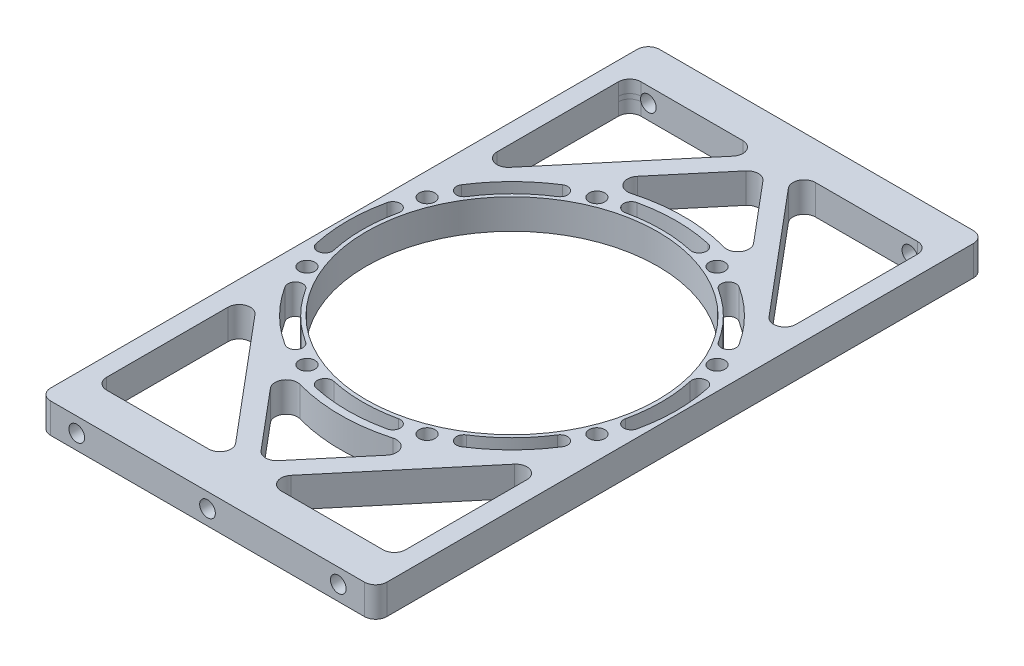
SolidWorks part; units mm, degrees
material "6063-O"
ref_plane "前视基准面" through (0, 0, 0) normal (0, 0, 1) x (1, 0, 0)
ref_plane "上视基准面" through (0, 0, 0) normal (0, 1, 0) x (1, 0, 0)
ref_plane "右视基准面" through (0, 0, 0) normal (1, 0, 0) x (0, 0, -1)
sketch "草图1" plane through (0, 0, 0) normal (0, 1, 0) x (1, 0, 0)
  line L1 (-45, 81.5) -> (45, 81.5)
  line L2 (-45, 81.5) -> (-45, -81.5)
  line L3 (-45, -81.5) -> (45, -81.5)
  line L4 (45, 81.5) -> (45, -81.5)
  line L5 (-45, 81.5) -> (45, -81.5) construction
  line L6 (-45, -81.5) -> (45, 81.5) construction
  circle A0 centre (0, 0) radius 39
  dimension "D1" = 78
  dimension "D2" = 90
  dimension "D3" = 163
extrude "凸台-拉伸1" add sketch "草图1" along normal mid plane 8
sketch "草图2" plane through (0, 4, 0) normal (0, 1, 0) x (1, 0, 0)
  line L0 (0, 0) -> (0, 42) construction
  line L1 (-16.0727, 38.8029) -> (0, 0) construction
  circle A0 centre (-16.0727, 38.8029) radius 1.9
  circle A1 centre (0, 0) radius 42 construction
  dimension "D1" = 84
  dimension "D2" = 3.8
  dimension "D3" = 22.5
extrude "切除-拉伸1" cut sketch "草图2" against normal through all
pattern_circular "阵列(圆周)1" count 8 over 360 about axis through (0, 0, 0) along (0, 1, 0) of "切除-拉伸1"
hole_wizard "M4 螺纹孔2" positions "3D草图2" profile "草图11" tap size "M5" standard "ISO" end condition through all
sketch3d "3D草图2"
  line L0 (16.0727, -4, -38.8029) -> (16.0727, 4, -38.8029) construction
  line L1 (38.8029, -4, -16.0727) -> (38.8029, 4, -16.0727) construction
  line L2 (38.8029, -4, 16.0727) -> (38.8029, 4, 16.0727) construction
  line L3 (16.0727, -4, 38.8029) -> (16.0727, 4, 38.8029) construction
  line L4 (-16.0727, -4, 38.8029) -> (-16.0727, 4, 38.8029) construction
  line L5 (-38.8029, -4, 16.0727) -> (-38.8029, 4, 16.0727) construction
  line L6 (-38.8029, -4, -16.0727) -> (-38.8029, 4, -16.0727) construction
  line L7 (-16.0727, -4, -38.8029) -> (-16.0727, 4, -38.8029) construction
  point P0 (16.0727, 4, -38.8029)
  point P4 (38.8029, 4, -16.0727)
  point P8 (38.8029, 4, 16.0727)
  point P12 (16.0727, 4, 38.8029)
  point P16 (-16.0727, 4, 38.8029)
  point P20 (-38.8029, 4, 16.0727)
  point P24 (-38.8029, 4, -16.0727)
  point P28 (-16.0727, 4, -38.8029)
sketch "草图11" plane through (16.0727, 4, -38.8029) normal (1, 0, 0) x (0, 0, 1)
  line L0 (0, 0) -> (0, 8)
  line L1 (0, 8) -> (2.1, 8)
  line L2 (2.1, 8) -> (2.1, 0)
  line L5 (2.1, 0) -> (0, 0)
  line L11 (0, -6.35) -> (0, 107.95) construction
  dimension "通孔螺纹孔钻头直径" = 4.2
  dimension "通孔螺纹孔钻头深度" = 8
cosmetic thread "孔螺蚊线13" parameters "D2"=5
cosmetic thread "孔螺蚊线14" parameters "D2"=5
cosmetic thread "孔螺蚊线15" parameters "D2"=5
cosmetic thread "孔螺蚊线16" parameters "D2"=5
cosmetic thread "孔螺蚊线17" parameters "D2"=5
cosmetic thread "孔螺蚊线18" parameters "D2"=5
cosmetic thread "孔螺蚊线19" parameters "D2"=5
cosmetic thread "孔螺蚊线20" parameters "D2"=5
sketch "草图12" plane through (0, 0, 81.5) normal (0, 0, 1) x (1, 0, 0)
  line L0 (-35, 0) -> (35, 0) construction
  circle A0 centre (0, 0) radius 2.1
  circle A1 centre (35, 0) radius 2.1
  circle A2 centre (-35, 0) radius 2.1
  point P2 (0, 0)
  dimension "D1" = 4.2
  dimension "D2" = 70
extrude "切除-拉伸2" cut sketch "草图12" against normal blind 5
hole_wizard "M5 螺纹孔1" positions "草图13" profile "草图14" tap size "M5" standard "ISO"
sketch "草图13" plane through (0, 0, 81.5) normal (0, 0, 1) x (1, 0, 0)
  point P0 (0, 0)
  point P3 (35, 0)
  point P6 (-35, 0)
sketch "草图14" plane through (0, 0, 81.5) normal (1, 0, 0) x (0, -1, 0)
  line L0 (0, 0) -> (0, 11.2618)
  line L1 (0, 11.2618) -> (2.1, 10)
  line L2 (2.1, 10) -> (2.1, 0)
  line L5 (2.1, 0) -> (0, 0)
  line L10 (0, 11.2618) -> (-2.1, 10) construction
  line L11 (0, -6.35) -> (0, 107.95) construction
  dimension "螺纹孔钻头直径" = 4.2
  dimension "螺纹孔钻头深度" = 10
  dimension "导头角度" = 118
cosmetic thread "孔螺蚊线21" parameters "D1"=10, "D2"=5
cosmetic thread "孔螺蚊线22" parameters "D1"=10, "D2"=5
cosmetic thread "孔螺蚊线23" parameters "D1"=10, "D2"=5
mirror "镜向1" about plane through (0, 0, 0) normal (0, 0, 1) of "切除-拉伸2", "M5 螺纹孔1"
cosmetic thread "孔螺蚊线24" parameters "D1"=10, "D2"=5
cosmetic thread "孔螺蚊线25" parameters "D1"=10, "D2"=5
cosmetic thread "孔螺蚊线26" parameters "D1"=10, "D2"=5
sketch "草图15" plane through (0, 4, 0) normal (0, 1, 0) x (1, 0, 0)
  line L0 (45, 71.5) -> (-45, 71.5)
  line L1 (-45, -71.5) -> (45, -71.5)
  line L2 (-40, 81.5) -> (-40, -81.5)
  line L3 (40, -81.5) -> (40, 81.5)
  line L4 (45, -81.5) -> (45, 81.5)
  line L5 (45, 81.5) -> (-45, 81.5)
  line L6 (-45, 81.5) -> (-45, -81.5)
  line L7 (-45, -81.5) -> (45, -81.5)
  line L8 (45, -81.5) -> (45, 81.5)
  line L9 (45, 81.5) -> (-45, 81.5)
  line L10 (-45, 81.5) -> (-45, -81.5)
  line L11 (-45, -81.5) -> (45, -81.5)
  line L12 (0, 71.5) -> (-35.2161, 29.5944)
  line L13 (0, 71.5) -> (0, 0) construction
  line L14 (0, 71.5) -> (35.2161, 29.5944)
  line L15 (0, 75.3859) -> (45, 21.8378)
  line L16 (0, 75.3859) -> (-45, 21.8378)
  line L17 (0, 67.6141) -> (33.3021, 27.986)
  line L18 (0, 67.6141) -> (-33.3021, 27.986)
  line L19 (0, 75.3859) -> (-37.13, 31.2028) construction
  line L20 (0, 75.3859) -> (37.13, 31.2028) construction
  line L21 (-45, 81.5) -> (-45, -81.5) construction
  line L22 (45, -81.5) -> (45, 81.5) construction
  circle A0 centre (0, 0) radius 46
  point P17 (0, 68.5594)
  point P25 (-47.7718, 18.5395)
  point P27 (49.0983, 16.961)
  point P29 (-45, 22.3321)
  point P32 (45, 21.8378)
  dimension "D1" = 92
  dimension "D2" = 0
  dimension "D3" = 10
  dimension "D4" = 5
  dimension "D5" = 2.5
  dimension "D6" = 2.5
extrude "切除-拉伸3" cut sketch "草图15" against normal blind 10 contours A0 L17 L18 | L0 L15 L3 | L16 L0 L2
mirror "镜向2" about plane through (0, 0, 0) normal (0, 0, 1) of "切除-拉伸3"
fillet "圆角1" radius 3 18 edges at (3.2656, 0, 71.5) (40, 0, 27.7876) (40, 0, 71.5) (0, 0, 67.6141) (-23.6786, 0, 39.4376) (23.6786, 0, 39.4376) (-23.6786, 0, -39.4376) (0, 0, -67.6141) (23.6786, 0, -39.4376) (40, 0, -27.7876) (3.2656, 0, -71.5) (40, 0, -71.5) (-40, 0, -27.7876) (-3.2656, 0, -71.5) (-40, 0, 71.5) (-40, 0, 27.7876) (-3.2656, 0, 71.5) (-40, 0, -71.5)
fillet "圆角2" radius 3 4 edges at (-45, 0, -81.5) (45, 0, -81.5) (45, 0, 81.5) (-45, 0, 81.5)
sketch "草图16" plane through (0, 4, 0) normal (0, 1, 0) x (1, 0, 0)
  line L0 (0, 42) -> (0, 0) construction
  line L1 (-9.0905, 41.0044) -> (0, 0) construction
  line L2 (0, 0) -> (9.0905, 41.0044) construction
  circle A0 centre (0, 0) radius 42 construction
  arc A1 (-9.0905, 41.0044) -> (9.0905, 41.0044) centre (0, 0) cw construction
  arc A2 (9.5233, 42.957) -> (-9.5233, 42.957) centre (0, 0) ccw
  arc A3 (8.6576, 39.0518) -> (-8.6576, 39.0518) centre (0, 0) ccw
  arc A4 (8.6576, 39.0518) -> (9.5233, 42.957) centre (9.0905, 41.0044) ccw
  arc A5 (-9.5233, 42.957) -> (-8.6576, 39.0518) centre (-9.0905, 41.0044) ccw
  arc A6 (22.5666, 35.4224) -> (35.4224, 22.5666) centre (0, 0) cw construction
  arc A7 (37.1092, 23.6412) -> (23.6412, 37.1092) centre (0, 0) ccw
  arc A8 (33.7357, 21.492) -> (21.492, 33.7357) centre (0, 0) ccw
  arc A9 (33.7357, 21.492) -> (37.1092, 23.6412) centre (35.4224, 22.5666) ccw
  arc A10 (23.6412, 37.1092) -> (21.492, 33.7357) centre (22.5666, 35.4224) ccw
  arc A11 (41.0044, 9.0905) -> (41.0044, -9.0905) centre (0, 0) cw construction
  arc A12 (42.957, -9.5233) -> (42.957, 9.5233) centre (0, 0) ccw
  arc A13 (39.0518, -8.6576) -> (39.0518, 8.6576) centre (0, 0) ccw
  arc A14 (39.0518, -8.6576) -> (42.957, -9.5233) centre (41.0044, -9.0905) ccw
  arc A15 (42.957, 9.5233) -> (39.0518, 8.6576) centre (41.0044, 9.0905) ccw
  arc A16 (35.4224, -22.5666) -> (22.5666, -35.4224) centre (0, 0) cw construction
  arc A17 (23.6412, -37.1092) -> (37.1092, -23.6412) centre (0, 0) ccw
  arc A18 (21.492, -33.7357) -> (33.7357, -21.492) centre (0, 0) ccw
  arc A19 (21.492, -33.7357) -> (23.6412, -37.1092) centre (22.5666, -35.4224) ccw
  arc A20 (37.1092, -23.6412) -> (33.7357, -21.492) centre (35.4224, -22.5666) ccw
  arc A21 (9.0905, -41.0044) -> (-9.0905, -41.0044) centre (0, 0) cw construction
  arc A22 (-9.5233, -42.957) -> (9.5233, -42.957) centre (0, 0) ccw
  arc A23 (-8.6576, -39.0518) -> (8.6576, -39.0518) centre (0, 0) ccw
  arc A24 (-8.6576, -39.0518) -> (-9.5233, -42.957) centre (-9.0905, -41.0044) ccw
  arc A25 (9.5233, -42.957) -> (8.6576, -39.0518) centre (9.0905, -41.0044) ccw
  arc A26 (-22.5666, -35.4224) -> (-35.4224, -22.5666) centre (0, 0) cw construction
  arc A27 (-37.1092, -23.6412) -> (-23.6412, -37.1092) centre (0, 0) ccw
  arc A28 (-33.7357, -21.492) -> (-21.492, -33.7357) centre (0, 0) ccw
  arc A29 (-33.7357, -21.492) -> (-37.1092, -23.6412) centre (-35.4224, -22.5666) ccw
  arc A30 (-23.6412, -37.1092) -> (-21.492, -33.7357) centre (-22.5666, -35.4224) ccw
  arc A31 (-41.0044, -9.0905) -> (-41.0044, 9.0905) centre (0, 0) cw construction
  arc A32 (-42.957, 9.5233) -> (-42.957, -9.5233) centre (0, 0) ccw
  arc A33 (-39.0518, 8.6576) -> (-39.0518, -8.6576) centre (0, 0) ccw
  arc A34 (-39.0518, 8.6576) -> (-42.957, 9.5233) centre (-41.0044, 9.0905) ccw
  arc A35 (-42.957, -9.5233) -> (-39.0518, -8.6576) centre (-41.0044, -9.0905) ccw
  arc A36 (-35.4224, 22.5666) -> (-22.5666, 35.4224) centre (0, 0) cw construction
  arc A37 (-23.6412, 37.1092) -> (-37.1092, 23.6412) centre (0, 0) ccw
  arc A38 (-21.492, 33.7357) -> (-33.7357, 21.492) centre (0, 0) ccw
  arc A39 (-21.492, 33.7357) -> (-23.6412, 37.1092) centre (-22.5666, 35.4224) ccw
  arc A40 (-37.1092, 23.6412) -> (-33.7357, 21.492) centre (-35.4224, 22.5666) ccw
  point P6 (0, 42)
  point P20 (29.6985, 29.6985)
  point P27 (42, 0)
  point P34 (29.6985, -29.6985)
  point P41 (0, -42)
  point P48 (-29.6985, -29.6985)
  point P55 (-42, 0)
  point P62 (-29.6985, 29.6985)
  point P67 (0, 0)
  dimension "D1" = 2
  dimension "D2" = 25
  dimension "D3" = 8
extrude "切除-拉伸4" cut sketch "草图16" against normal through all
